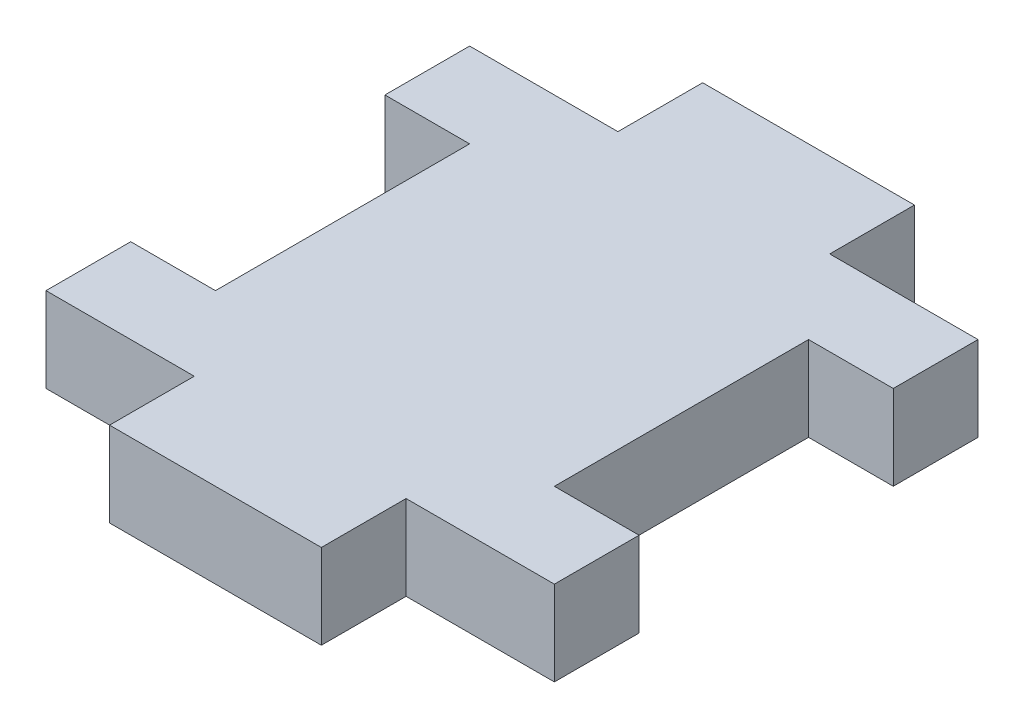
SolidWorks part; units mm, degrees
material "Acrylic (Medium-high impact)"
ref_plane "Front Plane" through (0, 0, 0) normal (0, 0, 1) x (1, 0, 0)
ref_plane "Top Plane" through (0, 0, 0) normal (0, 1, 0) x (1, 0, 0)
ref_plane "Right Plane" through (0, 0, 0) normal (1, 0, 0) x (0, 0, -1)
sketch "Sketch1" plane through (0, 0, 0) normal (0, 1, 0) x (1, 0, 0)
  line L0 (-15.875, -31.75) -> (-38.1, -31.75)
  line L1 (15.875, -44.45) -> (-15.875, -44.45)
  line L2 (15.875, -44.45) -> (15.875, -31.75)
  line L3 (15.875, 44.45) -> (-15.875, 44.45)
  line L4 (-15.875, -44.45) -> (-15.875, -31.75)
  line L5 (-15.875, 31.75) -> (-15.875, 44.45)
  line L6 (-15.875, 31.75) -> (-38.1, 31.75)
  line L7 (38.1, -31.75) -> (15.875, -31.75)
  line L8 (38.1, -31.75) -> (38.1, -19.05)
  line L9 (38.1, 31.75) -> (15.875, 31.75)
  line L10 (-38.1, -31.75) -> (-38.1, -19.05)
  line L11 (15.875, 31.75) -> (15.875, 44.45)
  line L12 (38.1, 19.05) -> (25.4, 19.05)
  line L13 (25.4, 19.05) -> (25.4, -19.05)
  line L14 (25.4, -19.05) -> (38.1, -19.05)
  line L15 (0, 6.8379) -> (0, -8.7746) construction
  line L16 (-25.4, -19.05) -> (-38.1, -19.05)
  line L17 (-38.1, 19.05) -> (-25.4, 19.05)
  line L18 (-25.4, 19.05) -> (-25.4, -19.05)
  line L19 (-38.1, 19.05) -> (-38.1, 31.75)
  line L20 (38.1, 19.05) -> (38.1, 31.75)
  point P0 (0, 0)
  point P6 (0, 0)
  point P15 (0, 44.45)
  point P17 (38.1, 0)
  point P19 (25.4, 0)
  dimension "D1" = 31.75
  dimension "D2" = 12.7
  dimension "D3" = 76.2
  dimension "D4" = 88.9
  dimension "D5" = 12.7
  dimension "D6" = 38.1
  dimension "D7" = 12.7
extrude "Boss-Extrude2" add sketch "Sketch1" along normal blind 12.7
